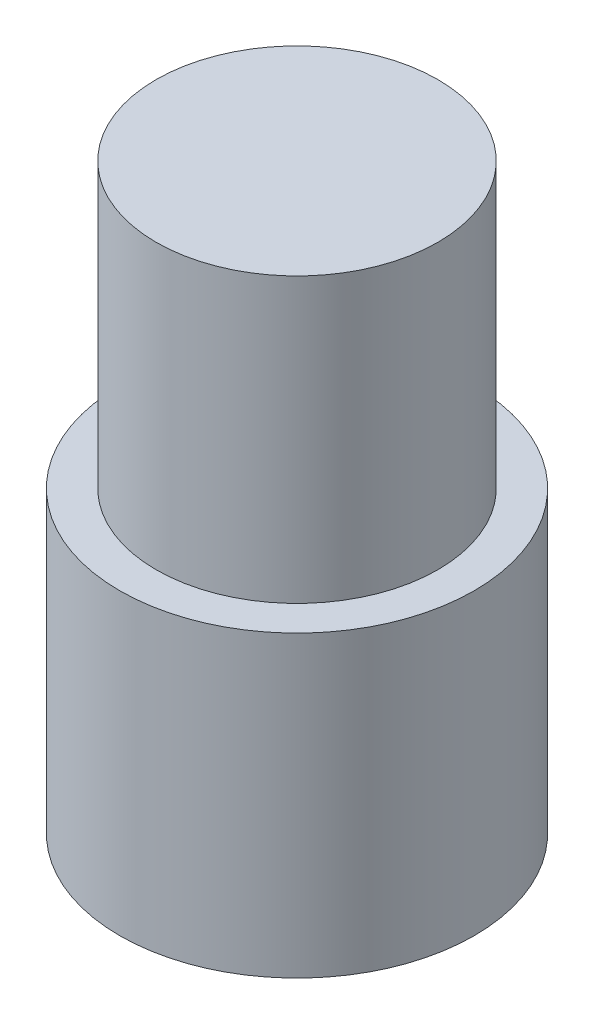
SolidWorks part; units mm, degrees
material "AISI 1020"
ref_plane "Front Plane" through (0, 0, 0) normal (0, 0, 1) x (1, 0, 0)
ref_plane "Top Plane" through (0, 0, 0) normal (0, 1, 0) x (1, 0, 0)
ref_plane "Right Plane" through (0, 0, 0) normal (1, 0, 0) x (0, 0, -1)
sketch "Sketch1" plane through (0, 0, 0) normal (1, 0, 0) x (0, 0, -1)
  line L0 (0, -2571.4363) -> (0, 126000.3802) construction
  line L1 (0, 101.1563) -> (39.75, 101.1563)
  line L2 (39.75, 101.1563) -> (39.75, 21.1563)
  line L3 (39.75, 21.1563) -> (50, 21.1563)
  line L7 (50, -63.1312) -> (0, -63.1312)
  line L8 (0, -63.1312) -> (0, 101.1563)
  line L9 (50, 21.1563) -> (50, -63.1312)
  dimension "D1" = 39.75
  dimension "D2" = 80
  dimension "D4" = 50
revolve "Revolve1" add sketch "Sketch1" angle 360 about L0
